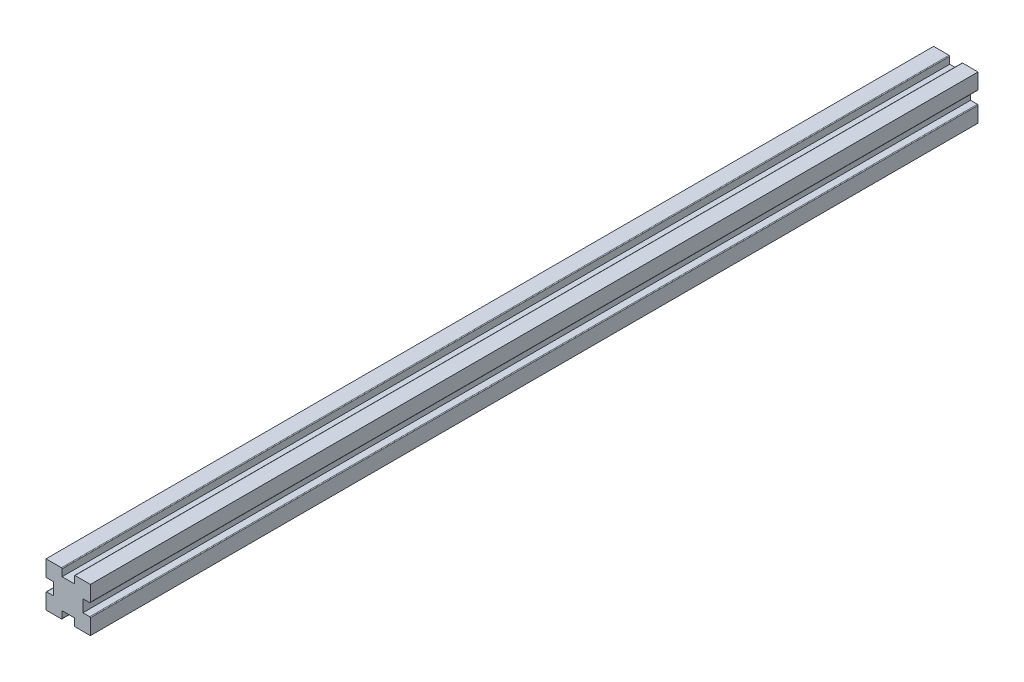
SolidWorks part; units mm, degrees
ref_plane "Front Plane" through (0, 0, 0) normal (0, 0, 1) x (1, 0, 0)
ref_plane "Top Plane" through (0, 0, 0) normal (0, 1, 0) x (1, 0, 0)
ref_plane "Right Plane" through (0, 0, 0) normal (1, 0, 0) x (0, 0, -1)
sketch "Sketch1" plane through (0, 0, 0) normal (0, 0, 1) x (1, 0, 0)
  line L0 (15.24, 4.185) -> (10.1082, 4.185)
  line L1 (-15.24, 15.24) -> (15.24, 15.24)
  line L2 (-15.24, 15.24) -> (-15.24, -15.24)
  line L3 (-15.24, -15.24) -> (15.24, -15.24)
  line L4 (15.24, 15.24) -> (15.24, -15.24)
  line L5 (-4.185, 15.24) -> (4.185, 15.24)
  line L6 (-4.185, 15.24) -> (-4.185, 10.1082)
  line L7 (-4.185, 10.1082) -> (4.185, 10.1082)
  line L8 (4.185, 15.24) -> (4.185, 10.1082)
  line L9 (15.24, 4.185) -> (15.24, -4.185)
  line L10 (15.24, -4.185) -> (10.1082, -4.185)
  line L11 (10.1082, 4.185) -> (10.1082, -4.185)
  line L12 (4.185, -15.24) -> (4.185, -10.1082)
  line L13 (4.185, -15.24) -> (-4.185, -15.24)
  line L14 (-4.185, -15.24) -> (-4.185, -10.1082)
  line L15 (4.185, -10.1082) -> (-4.185, -10.1082)
  line L16 (-15.24, -4.185) -> (-10.1082, -4.185)
  line L17 (-15.24, -4.185) -> (-15.24, 4.185)
  line L18 (-15.24, 4.185) -> (-10.1082, 4.185)
  line L19 (-10.1082, -4.185) -> (-10.1082, 4.185)
  circle A0 centre (0, 0) radius 15.24 construction
  point P4 (0, 15.24)
  point P6 (-15.24, 0)
  point P11 (0, 10.1082)
  point P29 (0, 0)
  dimension "D1" = 30.48
  dimension "D2" = 5.1318
  dimension "D3" = 8.37
  dimension "D4" = 4
extrude "Boss-Extrude1" add sketch "Sketch1" along normal blind 609.6 contours L19 L16 L2 L3 L14 L15 L12 L4 L10 L11 L0 L1 L8 L7 L6 L18
fillet "Fillet1" radius 0.5 8 edges at (-4.185, -15.24, 304.8) (4.185, -15.24, 304.8) (-15.24, -4.185, 304.8) (-15.24, 4.185, 304.8) (15.24, 4.185, 304.8) (15.24, -4.185, 304.8) (-4.185, 15.24, 304.8) (4.185, 15.24, 304.8)
